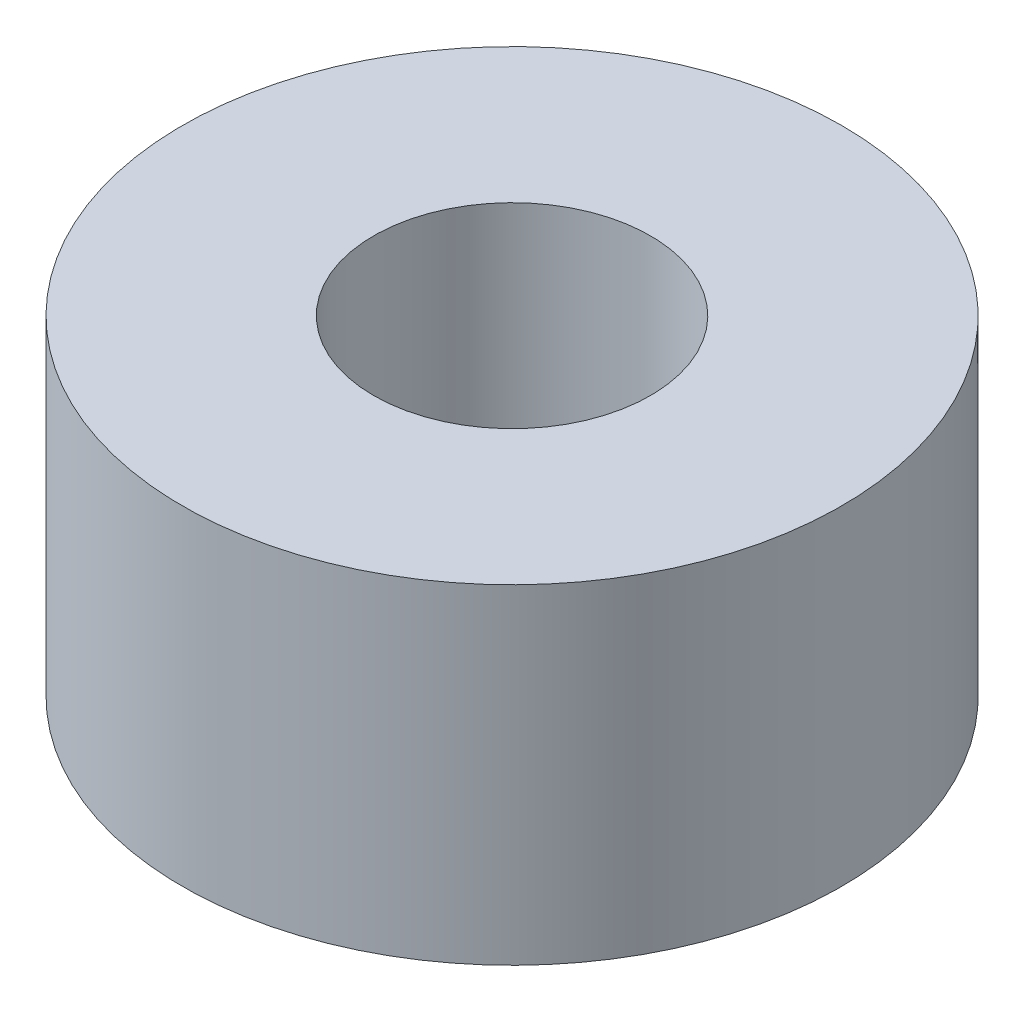
SolidWorks part; units mm, degrees
ref_plane "前视基准面" through (0, 0, 0) normal (0, 0, 1) x (1, 0, 0)
ref_plane "上视基准面" through (0, 0, 0) normal (0, 1, 0) x (1, 0, 0)
ref_plane "右视基准面" through (0, 0, 0) normal (1, 0, 0) x (0, 0, -1)
other "Configuration Table"
sketch "草图1" plane through (0, 0, 0) normal (0, 0, 1) x (1, 0, 0)
  line L0 (0, 0) -> (15, 0)
  line L1 (15, 0) -> (15, 15)
  line L2 (15, 15) -> (0, 15)
  line L3 (0, 15) -> (0, 0)
  line L4 (0, 0) -> (0, 15) construction
  dimension "radius" = 15
  dimension "height" = 15
revolve "Drive_mount_spacer" add sketch "草图1" angle 360 about L4
sketch "草图2" plane through (0, 15, 0) normal (0, 1, 0) x (1, 0, 0)
  circle A0 centre (0, 0) radius 6.3
  dimension "diameter" = 12.6
extrude "Shaft_passage" cut sketch "草图2" against normal through all
